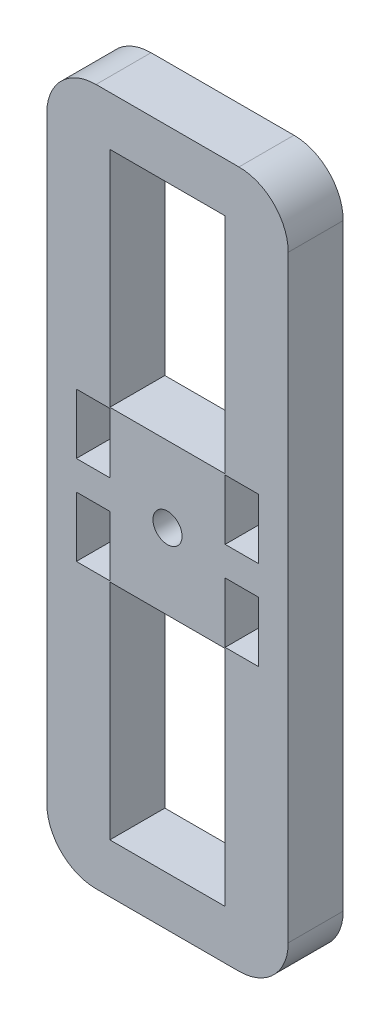
SolidWorks part; units mm, degrees
ref_plane "Front Plane" through (0, 0, 0) normal (0, 0, 1) x (1, 0, 0)
ref_plane "Top Plane" through (0, 0, 0) normal (0, 1, 0) x (1, 0, 0)
ref_plane "Right Plane" through (0, 0, 0) normal (1, 0, 0) x (0, 0, -1)
sketch "Sketch1" plane through (0, 0, 0) normal (0, 0, 1) x (1, 0, 0)
  line L0 (709.8457, 498.2992) -> (721.5457, 498.2992)
  line L1 (721.5457, 498.2992) -> (721.5457, 475.6297)
  line L2 (721.5457, 475.6297) -> (709.8457, 475.6297)
  line L3 (709.8457, 475.6297) -> (709.8457, 498.2992)
  line L4 (715.6957, 432.6102) -> (722.9457, 432.6102)
  line L5 (715.6957, 503.2992) -> (708.4457, 503.2992)
  line L6 (715.6957, 503.2992) -> (722.9457, 503.2992)
  line L7 (715.6957, 460.2797) -> (715.6957, 475.6297) construction
  line L8 (709.8457, 498.2992) -> (703.4457, 498.2992) construction
  line L9 (721.5457, 498.2992) -> (727.9457, 498.2992) construction
  line L10 (709.8457, 475.5297) -> (706.4457, 475.5297)
  line L11 (727.9457, 498.2992) -> (727.9457, 437.6102)
  line L12 (709.8457, 475.5297) -> (709.8457, 469.4297)
  line L13 (709.8457, 469.4297) -> (706.4457, 469.4297)
  line L14 (706.4457, 469.4297) -> (706.4457, 475.5297)
  line L15 (703.4457, 498.2992) -> (703.4457, 437.6102)
  line L16 (721.5457, 475.5297) -> (724.9457, 475.5297)
  line L17 (724.9457, 469.4297) -> (724.9457, 475.5297)
  line L18 (721.5457, 469.4297) -> (724.9457, 469.4297)
  line L19 (721.5457, 475.5297) -> (721.5457, 469.4297)
  line L20 (721.5457, 460.3797) -> (724.9457, 460.3797)
  line L21 (724.9457, 466.4797) -> (724.9457, 460.3797)
  line L22 (715.6957, 432.6102) -> (708.4457, 432.6102)
  line L24 (721.5457, 466.4797) -> (724.9457, 466.4797)
  line L25 (721.5457, 460.3797) -> (721.5457, 466.4797)
  line L26 (709.8457, 460.3797) -> (706.4457, 460.3797)
  line L27 (706.4457, 466.4797) -> (706.4457, 460.3797)
  line L28 (709.8457, 466.4797) -> (706.4457, 466.4797)
  line L29 (709.8457, 460.3797) -> (709.8457, 466.4797)
  line L30 (-282.9616, 469.4297) -> (49717.0384, 469.4297) construction
  line L31 (-282.9616, 466.4797) -> (49717.0384, 466.4797) construction
  line L37 (709.8457, 460.2797) -> (709.8457, 437.6102)
  line L38 (721.5457, 460.2797) -> (709.8457, 460.2797)
  line L39 (721.5457, 437.6102) -> (721.5457, 460.2797)
  line L40 (709.8457, 437.6102) -> (721.5457, 437.6102)
  line L171 (-296.4722, 467.9547) -> (49703.5278, 467.9547) construction
  circle A0 centre (715.6957, 467.9547) radius 1.475
  arc A1 (708.4457, 432.6102) -> (703.4457, 437.6102) centre (708.4457, 437.6102) cw
  arc A2 (708.4457, 503.2992) -> (703.4457, 498.2992) centre (708.4457, 498.2992) ccw
  arc A3 (722.9457, 503.2992) -> (727.9457, 498.2992) centre (722.9457, 498.2992) cw
  arc A4 (722.9457, 432.6102) -> (727.9457, 437.6102) centre (722.9457, 437.6102) ccw
  point P6 (715.6957, 504.6992)
  point P33 (715.6957, 475.6297)
  point P37 (715.6957, 467.9547)
  point P46 (715.6957, 431.2102)
  dimension "D1" = 6.1
  dimension "D4" = 2.95
  dimension "D2" = 3.4
  dimension "D3" = 0.1
  dimension "D5" = 22.6695
  dimension "D6" = 11.7
  dimension "D7" = 3
  dimension "D8" = 5
extrude "Boss-Extrude1" add sketch "Sketch1" along normal blind 5.58
